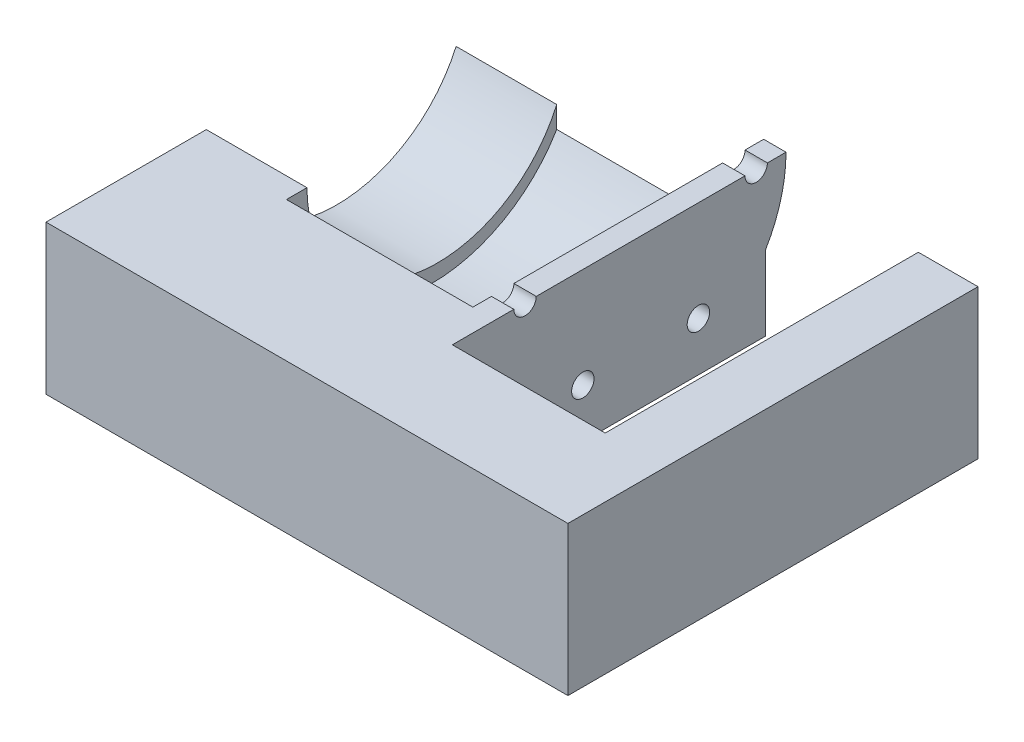
SolidWorks part; units mm, degrees
ref_plane "Front Plane" through (0, 0, 0) normal (0, 0, 1) x (1, 0, 0)
ref_plane "Top Plane" through (0, 0, 0) normal (0, 1, 0) x (1, 0, 0)
ref_plane "Right Plane" through (0, 0, 0) normal (1, 0, 0) x (0, 0, -1)
sketch "Sketch1" plane through (0, 0, 0) normal (0, 1, 0) x (1, 0, 0)
  line L1 (0, 0) -> (70, 0)
  line L2 (0, 0) -> (0, -55)
  line L3 (0, -55) -> (70, -55)
  line L4 (70, 0) -> (70, -55)
  dimension "D1" = 55
  dimension "D2" = 70
extrude "Boss-Extrude1" add sketch "Sketch1" along normal blind 20 contours L1 L4 L3 L2
ref_plane "Plane1" through (62, 0, 0) normal (1, 0, 0) x (0, 0, -1)
sketch "Sketch2" plane through (62, 0, 0) normal (1, 0, 0) x (0, 0, -1)
  line L0 (0, 0) -> (-55, 0) construction
  line L2 (-55, 20) -> (-55, 0) construction
  circle A0 centre (-16, 20) radius 26
  dimension "D1" = 52
  dimension "D2" = 20
  dimension "D3" = 39
extrude "Cut-Extrude1" cut sketch "Sketch2" against normal blind 20.5 contours A0
sketch "Sketch3" plane through (0, 0, 0) normal (-1, 0, 0) x (0, 0, 1)
  line L0 (0, 20) -> (55, 20) construction
  line L1 (55, 20) -> (55, 0) construction
  circle A0 centre (16, 20) radius 17.5
  dimension "D1" = 35
  dimension "D2" = 39
extrude "Cut-Extrude2" cut sketch "Sketch3" against normal blind 13.5 contours A0
sketch "Sketch5" plane through (13.5, 0, 0) normal (-1, 0, 0) x (0, 0, 1)
  line L0 (0, 20) -> (33.5, 20) construction
  circle A0 centre (16.75, 20) radius 19.5
  dimension "D1" = 39
extrude "Cut-Extrude3" cut sketch "Sketch5" against normal up to surface (28 mm away) up to face at (41.5, 9.7383, 19.2108)
ref_plane "Plane2" through (38.5, 0, 0) normal (1, 0, 0) x (0, 0, -1)
sketch "Sketch6" plane through (38.5, 0, 0) normal (1, 0, 0) x (0, 0, -1)
  line L0 (2.75, 20) -> (0.2531, 20)
  line L1 (-2.7531, 20) -> (-30.7469, 20)
  line L2 (-33.7531, 20) -> (-36.25, 20)
  arc A0 (-36.25, 20) -> (2.75, 20) centre (-16.75, 20) ccw
  arc A1 (-32.1771, 18.4987) -> (-1.3229, 18.4987) centre (-16.75, 20) ccw construction
  arc A2 (-2.7531, 20) -> (0.2531, 20) centre (-1.25, 20) ccw
  circle A3 centre (-9, 6.5766) radius 1.5031
  circle A4 centre (-24.5, 6.5766) radius 1.5031
  arc A5 (-33.7531, 20) -> (-30.7469, 20) centre (-32.25, 20) ccw
  point P14 (-16.75, 20)
  dimension "D1" = 39
  dimension "D2" = 31
  dimension "D3" = 3.0062
  dimension "D4" = 4
extrude "Boss-Extrude2" add sketch "Sketch6" along normal blind 3
